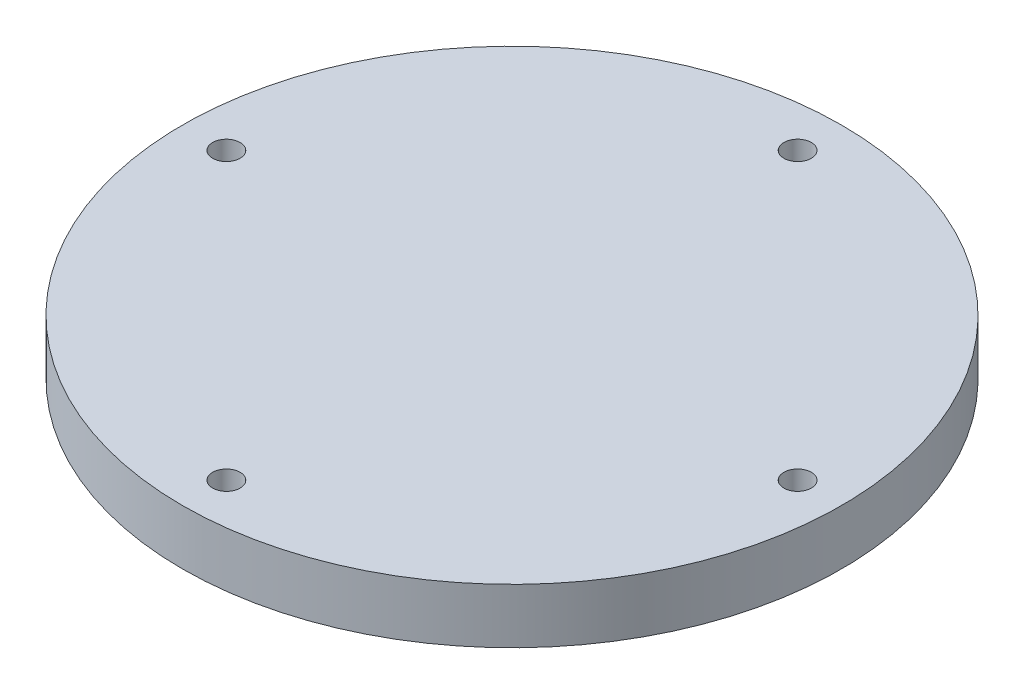
SolidWorks part; units mm, degrees
ref_plane "Front Plane" through (0, 0, 0) normal (0, 0, 1) x (1, 0, 0)
ref_plane "Top Plane" through (0, 0, 0) normal (0, 1, 0) x (1, 0, 0)
ref_plane "Right Plane" through (0, 0, 0) normal (1, 0, 0) x (0, 0, -1)
sketch "Sketch1" plane through (0, 0, 0) normal (0, 1, 0) x (1, 0, 0)
  circle A0 centre (0, 0) radius 38.1
  circle A1 centre (0, 33.02) radius 1.5875
  circle A2 centre (33.02, 0) radius 1.5875
  circle A3 centre (0, -33.02) radius 1.5875
  circle A4 centre (-33.02, 0) radius 1.5875
  point P14 (0, 0)
  dimension "D1" = 76.2
  dimension "D3" = 3.175
  dimension "D4" = 33.02
  dimension "D2" = 4
extrude "Boss-Extrude1" add sketch "Sketch1" along normal blind 6.35
